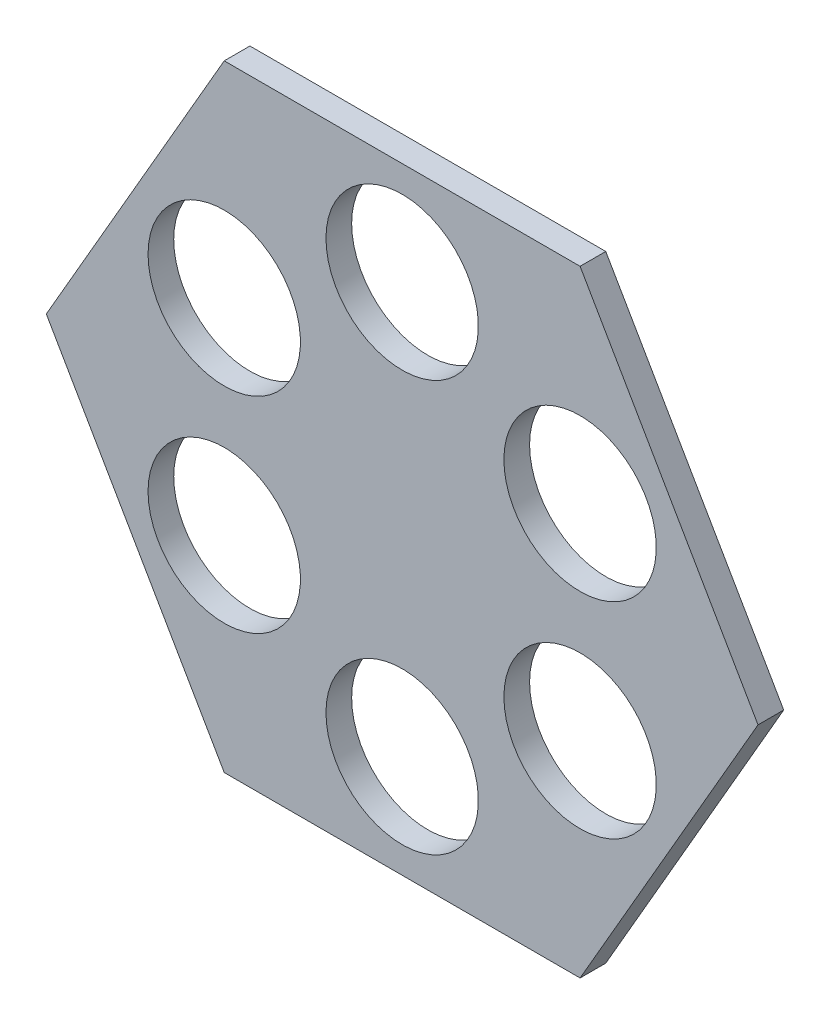
SolidWorks part; units mm, degrees
ref_plane "Front Plane" through (0, 0, 0) normal (0, 0, 1) x (1, 0, 0)
ref_plane "Top Plane" through (0, 0, 0) normal (0, 1, 0) x (1, 0, 0)
ref_plane "Right Plane" through (0, 0, 0) normal (1, 0, 0) x (0, 0, -1)
sketch "Sketch1" plane through (0, 0, 0) normal (0, 0, 1) x (1, 0, 0)
  line L0 (0, 0) -> (-131.9823, 228.6)
  line L1 (-131.9823, 228.6) -> (131.9823, 228.6)
  line L2 (131.9823, 228.6) -> (0, 0)
  line L3 (0, 0) -> (131.9823, 228.6)
  line L4 (131.9823, 228.6) -> (263.9645, 0)
  line L5 (263.9645, 0) -> (0, 0)
  line L6 (0, 0) -> (263.9645, 0)
  line L7 (263.9645, 0) -> (131.9823, -228.6)
  line L8 (131.9823, -228.6) -> (0, 0)
  line L9 (0, 0) -> (131.9823, -228.6)
  line L10 (131.9823, -228.6) -> (-131.9823, -228.6)
  line L11 (-131.9823, -228.6) -> (0, 0)
  line L12 (0, 0) -> (-131.9823, -228.6)
  line L13 (-131.9823, -228.6) -> (-263.9645, 0)
  line L14 (-263.9645, 0) -> (0, 0)
  line L15 (0, 0) -> (-263.9645, 0)
  line L16 (-263.9645, 0) -> (-131.9823, 228.6)
  line L17 (-131.9823, 228.6) -> (0, 0)
  circle A0 centre (0, 152.4) radius 56.515
  circle A1 centre (131.9823, 76.2) radius 56.515
  circle A2 centre (131.9823, -76.2) radius 56.515
  circle A3 centre (0, -152.4) radius 56.515
  circle A4 centre (-131.9823, -76.2) radius 56.515
  circle A5 centre (-131.9823, 76.2) radius 56.515
  point P29 (0, 0)
  dimension "D2" = 113.03
  dimension "D1" = 60
  dimension "D3" = 228.6
  dimension "D4" = 152.4
  dimension "D5" = 6
extrude "Boss-Extrude1" add sketch "Sketch1" along normal blind 19.05 contours L16 L14 L0 A5 | L2 L1 L0 A0 | L5 L4 L2 A1 | L8 L7 L5 A2 | L11 L10 L8 A3 | L14 L13 L11 A4
